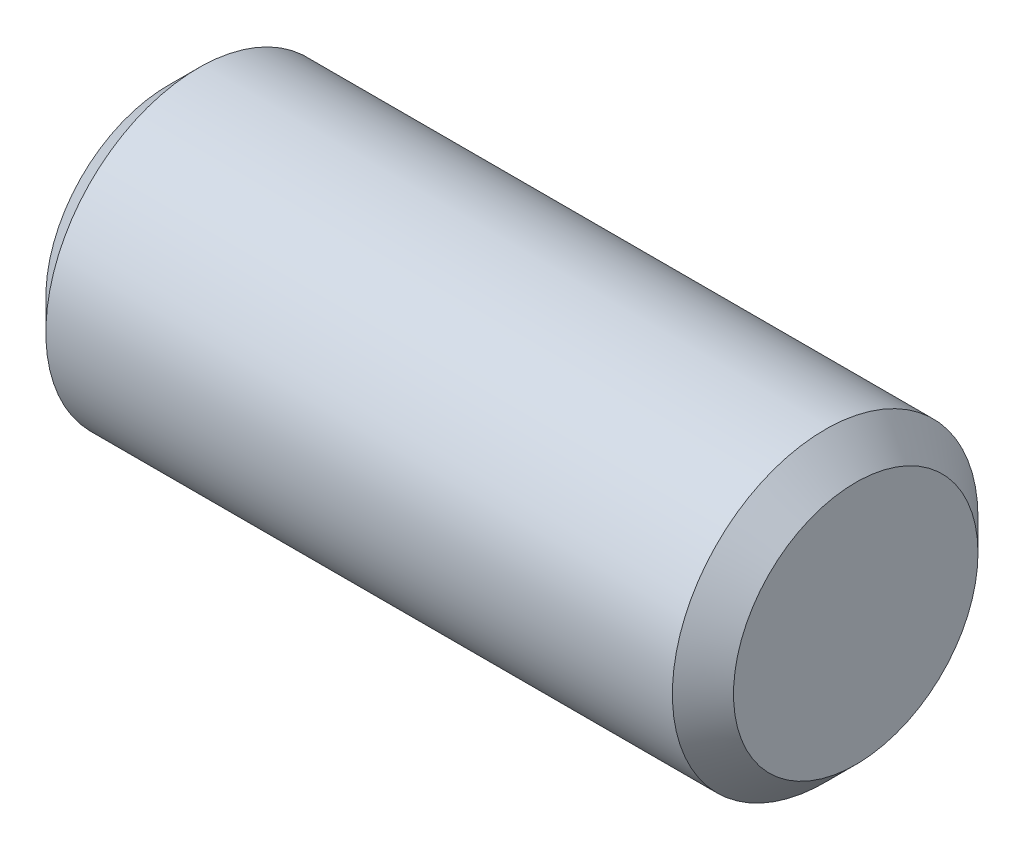
SolidWorks part; units mm, degrees
ref_plane "Front" through (0, 0, 0) normal (0, 0, 1) x (1, 0, 0)
ref_plane "Top" through (0, 0, 0) normal (0, 1, 0) x (1, 0, 0)
ref_plane "Right" through (0, 0, 0) normal (1, 0, 0) x (0, 0, -1)
sketch "Sketch1" plane through (0, 0, 0) normal (0, 0, 1) x (1, 0, 0)
  line L0 (-7.1437, 0) -> (7.1437, 0) construction
  line L1 (7.1438, 3.175) -> (7.1438, -3.175) construction
  line L2 (-7.1437, 3.175) -> (-7.1437, -3.175) construction
  dimension "Length" = 14.2875
  dimension "Diameter" = 6.35
sketch "Sketch2" plane through (0, 0, 0) normal (1, 0, 0) x (0, 0, -1)
  circle A0 centre (0, 0) radius 3.175
extrude "Extrude1" add sketch "Sketch2" against normal up to vertex (7.1437 mm away) and the other way up to vertex (7.1437 mm away) up to point (-7.1437, 3.175, 0) other way up to point (7.1438, 3.175, 0)
chamfer "Chamfer1" distance 0.635 angle 45 2 edges at (7.1438, 0, -3.175) (-7.1437, 0, -3.175)
equation "\"D1@Chamfer1\" = \"Diameter@Sketch1\"*.1"
